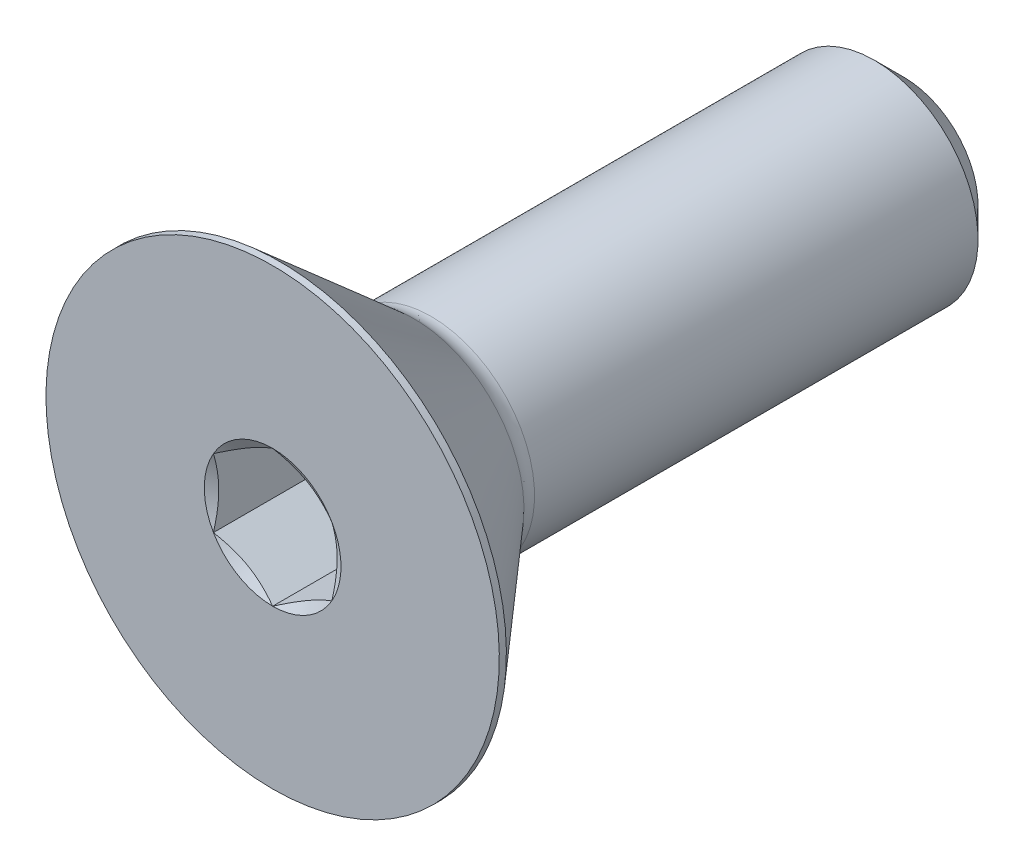
SolidWorks part; units mm, degrees
material "Plain Carbon Steel"
ref_plane "Front" through (0, 0, 0) normal (0, 0, 1) x (1, 0, 0)
ref_plane "Top" through (0, 0, 0) normal (0, 1, 0) x (1, 0, 0)
ref_plane "Right" through (0, 0, 0) normal (1, 0, 0) x (0, 0, -1)
sketch "Sketch1" plane through (0, 0, 0) normal (1, 0, 0) x (0, 0, -1)
  line L0 (0, 4.5593) -> (0.1422, 4.5593) construction
  line L1 (0.1422, 4.5593) -> (2.8448, 2.21) construction
  line L2 (0, 2.0828) -> (12.7, 2.0828)
  line L3 (12.7, 2.0828) -> (12.7, 0)
  line L4 (12.7, 0) -> (0, 0)
  line L5 (0, 0) -> (0, 4.5593) construction
  line L6 (0, 4.5593) -> (0, -4.5593) construction
  line L7 (12.7, 2.0828) -> (12.7, -2.0828) construction
  line L8 (0, -4.5593) -> (0.1422, -4.5593) construction
  line L9 (0.1422, -4.5593) -> (2.8448, -2.21) construction
  line L11 (0, 2.0828) -> (0, 0)
  line L12 (3.185, 2.0828) -> (3.185, 0) construction
  line L13 (-12.7, 0) -> (-12.7, 2.0828) construction
  arc A1 (2.8448, 2.21) -> (3.185, 2.0828) centre (3.185, 2.6014) ccw construction
  dimension "Min Thread" = 25.4
revolve "Revolve1" add sketch "Sketch1" angle 360 mid plane about L4
ref_plane "Plane2" through (0, 0, 12.7) normal (0, 0, 1) x (1, 0, 0)
chamfer "Chamfer1" distance 0.5953 angle 45 1 edges at (0, 2.0828, -12.7)
sketch "Sketch7" plane through (0, 0, 0) normal (1, 0, 0) x (0, 0, -1)
  line L0 (0, 4.5593) -> (0.1422, 4.5593) construction
  line L1 (0.1422, 4.5593) -> (2.8448, 2.21) construction
  line L2 (0, 4.5593) -> (0.1422, 4.5593)
  line L3 (0.1422, 4.5593) -> (2.8448, 2.21)
  line L4 (3.185, 2.0828) -> (3.185, 0) construction
  line L5 (3.185, 2.0828) -> (3.185, 0)
  line L7 (0, 0) -> (0, 4.5593) construction
  line L8 (0, 0) -> (0, 4.5593)
  line L9 (0, 0) -> (3.185, 0)
  line L10 (3.5623, 0) -> (-3.5623, 0) construction
  arc A0 (2.8448, 2.21) -> (3.185, 2.0828) centre (3.185, 2.6014) ccw construction
  arc A1 (2.8448, 2.21) -> (3.185, 2.0828) centre (3.185, 2.6014) ccw
revolve "Revolve2" add sketch "Sketch7" angle 360 mid plane about L9
ref_plane "Plane1" through (0, 0, -3.185) normal (0, 0, 1) x (1, 0, 0)
sketch "Sketch5" plane through (0, 0, 0) normal (0, 0, 1) x (1, 0, 0)
  line L0 (0, 0) -> (-1.3748, 0) construction
  line L1 (0, 0) -> (-2.7496, 1.5875) construction
  line L2 (0, 0) -> (-2.7496, -1.5875) construction
  line L6 (0, 1.3748) -> (0, 1.1339) construction
  line L7 (0, 1.1339) -> (0, 0.893) construction
  line L9 (0, 1.3748) -> (-1.1906, 0.6874)
  line L10 (-1.1906, 0.6874) -> (-1.1906, -0.6874)
  line L11 (-1.1906, -0.6874) -> (0, -1.3748)
  line L12 (0, -1.3748) -> (1.1906, -0.6874)
  line L13 (1.1906, -0.6874) -> (1.1906, 0.6874)
  line L14 (1.1906, 0.6874) -> (0, 1.3748)
  circle A0 centre (0, 0) radius 1.3748 construction
  circle A1 centre (0, 0) radius 1.1339 construction
  circle A2 centre (0, 0) radius 0.893 construction
  circle A3 centre (0, 0) radius 1.1906 construction
  dimension "D3" = 1.7859
  dimension "D4" = 30
  dimension "D5" = 30
extrude "Cut-Extrude2" cut sketch "Sketch5" against normal blind 1.9914
sketch "Sketch6" plane through (0, 0, 0) normal (0, 0, 1) x (1, 0, 0)
  circle A0 centre (0, 0) radius 1.3748
extrude "Cut-Extrude3" cut sketch "Sketch6" against normal blind 1.9914 draft 60
sketch "Sketch9" [suppressed] plane through (0, 0, -3.6076) normal (0, 0, 1) x (1, 0, 0)
  circle A1 centre (0, 0) radius 2.413
  circle A2 centre (0, 0) radius 2.413
  point P0 (0, 2.413)
  dimension "D1" = 0
extrude "Boss-Extrude2" [suppressed] add sketch "Sketch9" against normal up to surface (15.4424 mm away)
equation "\"D1@Cut-Extrude2\" = \"Head Ht@Sketch1\" * .7"
equation "\"D1@Sketch1\" = \"Head Ht@Sketch1\" * .05"
equation "\"D1@Cut-Extrude3\" = \"D1@Cut-Extrude2\""
equation "\"D3@Sketch5\" = \"Hex@Sketch5\" * .75"
